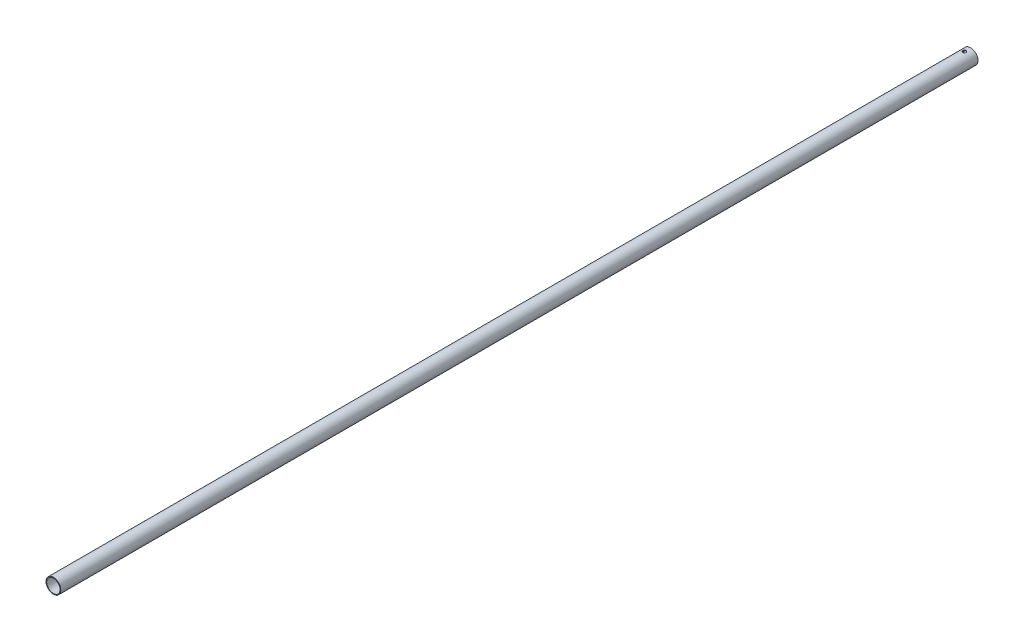
SolidWorks part; units mm, degrees
material "Plain Carbon Steel"
ref_plane "Front Plane" through (0, 0, 0) normal (0, 0, 1) x (1, 0, 0)
ref_plane "Top Plane" through (0, 0, 0) normal (0, 1, 0) x (1, 0, 0)
ref_plane "Right Plane" through (0, 0, 0) normal (1, 0, 0) x (0, 0, -1)
sketch "Sketch1" plane through (0, 0, 0) normal (0, 0, 1) x (1, 0, 0)
  circle A0 centre (0, 0) radius 14.732
  circle A1 centre (0, 0) radius 13.3096
  dimension "D1" = 1.4224
  dimension "D2" = 29.464
extrude "Extrude1" add sketch "Sketch1" along normal blind 1828.8
ref_plane "Plane1" through (0, -14.732, 914.4) normal (0, -1, 0) x (-1, 0, 0)
sketch "Sketch2" plane through (0, -14.732, 914.4) normal (0, -1, 0) x (-1, 0, 0)
  line L0 (0, 914.4) -> (0, 901.7) construction
  dimension "D1" = 12.7
hole_wizard "1/4 Clearance Hole2" positions "Sketch7" profile "Sketch8" hole size "1/4" standard "Ansi Inch" end condition through all
sketch "Sketch7" plane through (0, -14.732, 914.4) normal (0, -1, 0) x (-1, 0, 0)
  point P1 (0, 901.7)
sketch "Sketch8" plane through (0, -14.732, 12.7) normal (1, 0, 0) x (0, 0, -1)
  line L0 (0, 0) -> (0, 29.464)
  line L1 (0, 29.464) -> (3.3782, 29.464)
  line L2 (3.3782, 29.464) -> (3.3782, 0)
  line L5 (3.3782, 0) -> (0, 0)
  line L11 (0, -6.35) -> (0, 107.95) construction
  dimension "Thru Hole Dia." = 6.7564
  dimension "Thru Hole Depth" = 29.464
